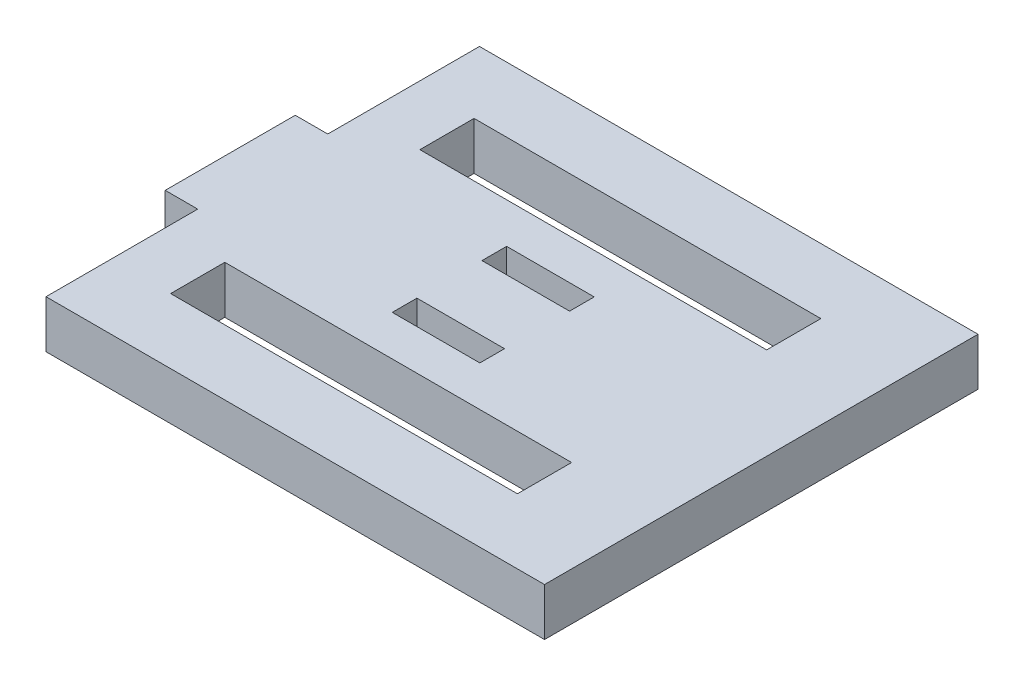
SolidWorks part; units mm, degrees
material "cardboard"
ref_plane "Front Plane" through (0, 0, 0) normal (0, 0, 1) x (1, 0, 0)
ref_plane "Top Plane" through (0, 0, 0) normal (0, 1, 0) x (1, 0, 0)
ref_plane "Right Plane" through (0, 0, 0) normal (1, 0, 0) x (0, 0, -1)
sketch "Sketch1" plane through (0, 0, 0) normal (0, 1, 0) x (1, 0, 0)
  line L0 (78.5546, 12.1341) -> (71.7044, 8.1792)
  line L1 (104.0546, -11.8659) -> (110.9047, -7.911)
  line L2 (119.2044, 8.1792) -> (110.9047, 8.1792)
  line L3 (119.2044, -7.911) -> (110.9047, -7.911)
  line L4 (71.7044, 8.1792) -> (63.4047, 8.1792)
  line L5 (126.0546, 12.1341) -> (119.2044, 8.1792)
  line L6 (126.0546, -11.8659) -> (119.2044, -7.911)
  line L7 (104.0546, 12.1341) -> (110.9047, 8.1792)
  line L8 (126.0546, 12.1341) -> (138.8046, 12.1341)
  line L9 (126.0546, -11.8659) -> (162.8046, -11.8659)
  line L10 (56.5546, 12.1341) -> (63.4047, 8.1792)
  line L11 (56.5546, -11.8659) -> (63.4047, -7.911)
  line L12 (78.5546, -11.8659) -> (71.7044, -7.911)
  line L13 (71.7044, -7.911) -> (63.4047, -7.911)
  line L14 (78.5546, 12.1341) -> (104.0546, 12.1341)
  line L15 (78.5546, -11.8659) -> (104.0546, -11.8659)
  line L16 (-11.1954, 77.8841) -> (-7.2405, 71.034)
  line L17 (12.8046, 103.3841) -> (8.8496, 110.2342)
  line L18 (-7.2405, 118.534) -> (-7.2405, 110.2342)
  line L19 (8.8496, 118.534) -> (8.8496, 110.2342)
  line L20 (-7.2405, 71.034) -> (-7.2405, 62.7342)
  line L21 (-11.1954, 125.3841) -> (-7.2405, 118.534)
  line L22 (12.8046, 125.3841) -> (8.8496, 118.534)
  line L23 (-11.1954, 103.3841) -> (-7.2405, 110.2342)
  line L24 (-11.1954, 125.3841) -> (-11.1954, 138.1341)
  line L25 (12.8046, 125.3841) -> (12.8046, 162.1341)
  line L26 (-11.1954, 55.8841) -> (-7.2405, 62.7342)
  line L27 (12.8046, 55.8841) -> (8.8496, 62.7342)
  line L28 (12.8046, 77.8841) -> (8.8496, 71.034)
  line L29 (8.8496, 71.034) -> (8.8496, 62.7342)
  line L30 (-11.1954, 77.8841) -> (-11.1954, 103.3841)
  line L31 (12.8046, 77.8841) -> (12.8046, 103.3841)
  line L32 (91.3046, 37.1341) -> (91.3046, 17.1341)
  line L33 (90.3046, 37.1341) -> (90.3046, 31.1341)
  line L34 (37.8046, 12.1341) -> (43.8046, 12.1341)
  line L35 (90.3046, 31.1341) -> (92.3046, 31.1341)
  line L36 (42.5546, 12.1341) -> (42.5546, 10.1341)
  line L37 (43.8046, 12.1341) -> (56.5546, 12.1341)
  line L38 (138.8046, 12.1341) -> (138.8046, -11.8659)
  line L39 (138.8046, 12.1341) -> (162.8046, 12.1341)
  line L40 (162.8046, 12.1341) -> (162.8046, 10.1341)
  line L41 (-27.6918, 14.4884) -> (0.8046, -14.008)
  line L42 (-27.6918, 14.4884) -> (-13.5497, 28.6305)
  line L43 (0.8046, -14.008) -> (14.9467, 0.1341)
  line L44 (-13.5497, 28.6305) -> (14.9467, 0.1341)
  line L45 (138.8046, 12.1341) -> (138.8046, 37.1341)
  line L46 (40.8046, 37.1341) -> (162.8046, 37.1341)
  line L47 (162.8046, 37.1341) -> (162.8046, 12.1341)
  line L48 (92.3046, 31.1341) -> (92.3046, 23.1341)
  line L49 (138.8046, 37.1341) -> (138.8046, 61.1341)
  line L50 (138.8046, 61.1341) -> (147.8046, 61.1341)
  line L51 (43.8046, 37.1341) -> (43.8046, 17.1341)
  line L52 (162.8046, 61.1341) -> (162.8046, 51.4561)
  line L53 (147.8046, 61.1341) -> (147.8046, 63.3341)
  line L54 (153.8046, 63.3341) -> (153.8046, 61.1341)
  line L55 (153.8046, 61.1341) -> (162.8046, 61.1341)
  line L56 (-58.1954, 138.1341) -> (-58.1954, 113.6341)
  line L57 (-38.1954, 113.6341) -> (-38.1954, 138.1341)
  line L58 (92.3046, 23.1341) -> (90.3046, 23.1341)
  line L59 (138.8046, -11.8659) -> (138.8046, -36.8659)
  line L60 (147.8046, -36.8659) -> (153.8046, -36.8659)
  line L61 (162.8046, -36.8659) -> (162.8046, -11.8659)
  line L62 (43.8046, -36.8659) -> (43.8046, -16.8659)
  line L63 (138.8046, -36.8659) -> (138.8046, -38.0459)
  line L64 (153.8046, -38.0459) -> (162.8046, -38.0459)
  line L65 (162.8046, -38.0459) -> (162.8046, -36.8659)
  line L66 (147.8046, -38.0459) -> (147.8046, -36.8659)
  line L67 (153.8046, -38.0459) -> (153.8046, -36.8659)
  line L68 (-37.3754, -137.8659) -> (-37.3754, -146.8659)
  line L69 (90.3046, 23.1341) -> (90.3046, 17.1341)
  line L70 (90.3046, 12.1341) -> (90.3046, 4.1341)
  line L71 (43.8046, -11.8659) -> (56.5546, -11.8659)
  line L72 (37.8046, -11.8659) -> (43.8046, -11.8659)
  line L73 (91.2784, 12.1341) -> (91.2784, -11.8659)
  line L74 (90.3046, 4.1341) -> (92.3046, 4.1341)
  line L75 (92.3046, 4.1341) -> (92.3046, -3.8659)
  line L76 (92.3046, -3.8659) -> (90.3046, -3.8659)
  line L77 (136.8046, 12.1341) -> (136.8046, 4.1341)
  line L78 (136.8046, 4.1341) -> (140.8046, 4.1341)
  line L79 (38.9846, 162.1341) -> (38.9846, 153.1341)
  line L80 (38.8046, 35.1341) -> (38.8046, 19.1341)
  line L81 (40.8046, 17.1341) -> (138.8046, 17.1341)
  line L82 (42.5546, 24.1341) -> (42.5546, 17.1341)
  line L83 (43.8046, 30.1341) -> (40.8046, 30.1341)
  line L84 (40.8046, 30.1341) -> (40.8046, 24.1341)
  line L85 (45.0546, 6.1341) -> (42.5546, 6.1341)
  line L86 (6.8046, -41.6159) -> (6.8046, -39.6159)
  line L87 (42.5546, -5.8659) -> (45.0546, -5.8659)
  line L88 (45.0546, 6.1341) -> (45.0546, -5.8659)
  line L89 (43.8046, 12.1341) -> (43.8046, 6.1341)
  line L90 (42.5546, 10.1341) -> (45.0546, 10.1341)
  line L91 (45.0546, 10.1341) -> (45.0546, 8.1341)
  line L92 (45.0546, 8.1341) -> (42.5546, 8.1341)
  line L93 (42.5546, 8.1341) -> (42.5546, 6.1341)
  line L94 (42.5546, -7.8659) -> (42.5546, -5.8659)
  line L95 (45.0546, -7.8659) -> (42.5546, -7.8659)
  line L96 (45.0546, -9.8659) -> (45.0546, -7.8659)
  line L97 (42.5546, -9.8659) -> (45.0546, -9.8659)
  line L98 (42.5546, -11.8659) -> (42.5546, -9.8659)
  line L99 (140.8046, 4.1341) -> (140.8046, -3.8659)
  line L100 (140.8046, -3.8659) -> (136.8046, -3.8659)
  line L101 (136.8046, -3.8659) -> (136.8046, -11.8659)
  line L102 (138.8046, 14.1341) -> (146.8046, 14.1341)
  line L103 (146.8046, 14.1341) -> (146.8046, 10.1341)
  line L104 (146.8046, 10.1341) -> (154.8046, 10.1341)
  line L105 (154.8046, 10.1341) -> (154.8046, 14.1341)
  line L106 (154.8046, 14.1341) -> (162.8046, 14.1341)
  line L107 (137.3046, 37.1341) -> (137.3046, 31.1341)
  line L108 (137.3046, 31.1341) -> (140.3046, 31.1341)
  line L109 (140.3046, 31.1341) -> (140.3046, 23.1341)
  line L110 (140.3046, 23.1341) -> (137.3046, 23.1341)
  line L111 (137.3046, 23.1341) -> (137.3046, 17.1341)
  line L112 (90.3046, -3.8659) -> (90.3046, -11.8659)
  line L113 (90.3046, -22.8659) -> (90.3046, -16.8659)
  line L114 (91.3046, -36.8659) -> (91.3046, -16.8659)
  line L115 (92.3046, -22.8659) -> (90.3046, -22.8659)
  line L116 (92.3046, -30.8659) -> (92.3046, -22.8659)
  line L117 (154.8046, -13.8659) -> (162.8046, -13.8659)
  line L118 (154.8046, -9.8659) -> (154.8046, -13.8659)
  line L119 (146.8046, -9.8659) -> (154.8046, -9.8659)
  line L120 (146.8046, -13.8659) -> (146.8046, -9.8659)
  line L121 (138.8046, -13.8659) -> (146.8046, -13.8659)
  line L122 (137.3046, -22.8659) -> (137.3046, -16.8659)
  line L123 (140.3046, -22.8659) -> (137.3046, -22.8659)
  line L124 (42.5546, 37.1341) -> (42.5546, 30.1341)
  line L125 (43.8046, 24.1341) -> (40.8046, 24.1341)
  line L126 (138.8046, -36.8659) -> (40.8046, -36.8659)
  line L127 (38.8046, -34.8659) -> (38.8046, -18.8659)
  line L128 (40.8046, -16.8659) -> (138.8046, -16.8659)
  line L129 (140.3046, -30.8659) -> (140.3046, -22.8659)
  line L130 (137.3046, -30.8659) -> (140.3046, -30.8659)
  line L131 (137.3046, -36.8659) -> (137.3046, -30.8659)
  line L132 (90.3046, -30.8659) -> (92.3046, -30.8659)
  line L133 (90.3046, -36.8659) -> (90.3046, -30.8659)
  line L134 (138.8046, 39.1341) -> (146.8046, 39.1341)
  line L135 (146.8046, 39.1341) -> (146.8046, 35.1341)
  line L136 (146.8046, 35.1341) -> (154.8046, 35.1341)
  line L137 (154.8046, 35.1341) -> (154.8046, 39.1341)
  line L138 (154.8046, 39.1341) -> (162.8046, 39.1341)
  line L139 (-43.6954, 133.8841) -> (-43.6954, 117.8841)
  line L140 (-55.1954, 133.8841) -> (-52.6954, 133.8841)
  line L141 (-55.1954, 133.8841) -> (-55.1954, 117.8841)
  line L142 (-55.1954, 117.8841) -> (-52.6954, 117.8841)
  line L143 (-52.6954, 133.8841) -> (-52.6954, 117.8841)
  line L144 (42.5546, -23.8659) -> (42.5546, -16.8659)
  line L145 (43.8046, -23.8659) -> (40.8046, -23.8659)
  line L146 (40.8046, -29.8659) -> (40.8046, -23.8659)
  line L147 (43.8046, -29.8659) -> (40.8046, -29.8659)
  line L148 (42.5546, -36.8659) -> (42.5546, -29.8659)
  line L149 (197.8046, 5.1341) -> (197.8046, -4.8659)
  line L150 (192.8046, 10.1341) -> (162.8046, 10.1341)
  line L151 (192.8046, -9.8659) -> (162.8046, -9.8659)
  line L152 (192.8046, 10.1341) -> (197.8046, 5.1341)
  line L153 (197.8046, -4.8659) -> (192.8046, -9.8659)
  line L154 (162.8046, -9.8659) -> (162.8046, -11.8659)
  line L155 (138.8046, 63.3341) -> (147.8046, 63.3341)
  line L156 (138.8046, 63.3341) -> (138.8046, 65.3341)
  line L157 (138.8046, 65.3341) -> (162.8046, 65.3341)
  line L158 (162.8046, 65.3341) -> (162.8046, 63.3341)
  line L159 (153.8046, 63.3341) -> (162.8046, 63.3341)
  line L160 (-41.1954, 117.8841) -> (-43.6954, 117.8841)
  line L161 (-41.1954, 133.8841) -> (-41.1954, 117.8841)
  line L162 (-41.1954, 133.8841) -> (-43.6954, 133.8841)
  line L163 (156.2046, 51.4561) -> (162.8046, 51.4561)
  line L164 (156.2046, 51.4561) -> (156.2046, 46.9561)
  line L165 (156.2046, 46.9561) -> (162.8046, 46.9561)
  line L166 (162.8046, 46.9561) -> (162.8046, 37.1341)
  line L167 (12.8046, -77.6159) -> (8.8496, -70.7658)
  line L168 (-11.1954, -103.1159) -> (-7.2405, -109.966)
  line L169 (8.8496, -118.2658) -> (8.8496, -109.966)
  line L170 (12.8046, -36.8659) -> (12.8046, -42.8659)
  line L171 (12.8046, -41.6159) -> (10.8046, -41.6159)
  line L172 (12.8046, -42.8659) -> (12.8046, -55.6159)
  line L173 (-7.2405, -118.2658) -> (-7.2405, -109.966)
  line L174 (8.8496, -70.7658) -> (8.8496, -62.466)
  line L175 (12.8046, -125.1159) -> (8.8496, -118.2658)
  line L176 (-11.1954, -125.1159) -> (-7.2405, -118.2658)
  line L177 (12.8046, -103.1159) -> (8.8496, -109.966)
  line L178 (12.8046, -125.1159) -> (12.8046, -137.8659)
  line L179 (-11.1954, -125.1159) -> (-11.1954, -161.8659)
  line L180 (12.8046, -55.6159) -> (8.8496, -62.466)
  line L181 (-11.1954, -55.6159) -> (-7.2405, -62.466)
  line L182 (37.8046, -42.8659) -> (17.8046, -42.8659)
  line L183 (-11.1954, -77.6159) -> (-7.2405, -70.7658)
  line L184 (-7.2405, -70.7658) -> (-7.2405, -62.466)
  line L185 (12.8046, -77.6159) -> (12.8046, -103.1159)
  line L186 (-11.1954, -77.6159) -> (-11.1954, -103.1159)
  line L187 (37.8046, -90.3659) -> (17.8046, -90.3659)
  line L188 (37.8046, -89.3659) -> (31.8046, -89.3659)
  line L189 (31.8046, -89.3659) -> (31.8046, -91.3659)
  line L190 (12.8046, -137.8659) -> (-11.1954, -137.8659)
  line L191 (12.8046, -137.8659) -> (12.8046, -161.8659)
  line L192 (12.8046, -161.8659) -> (10.8046, -161.8659)
  line L193 (12.8046, -137.8659) -> (37.8046, -137.8659)
  line L194 (37.8046, -39.8659) -> (37.8046, -161.8659)
  line L195 (-36.1954, -42.8659) -> (-16.1954, -42.8659)
  line L196 (37.8046, -161.8659) -> (12.8046, -161.8659)
  line L197 (31.8046, -91.3659) -> (23.8046, -91.3659)
  line L198 (37.8046, -137.8659) -> (61.8046, -137.8659)
  line L199 (61.8046, -137.8659) -> (61.8046, -146.8659)
  line L200 (61.8046, -161.8659) -> (52.1265, -161.8659)
  line L201 (61.8046, -146.8659) -> (64.0046, -146.8659)
  line L202 (64.0046, -152.8659) -> (61.8046, -152.8659)
  line L203 (61.8046, -152.8659) -> (61.8046, -161.8659)
  line L204 (-11.1954, -42.8659) -> (-11.1954, -55.6159)
  line L205 (-11.1954, -36.8659) -> (-11.1954, -42.8659)
  line L206 (23.8046, -91.3659) -> (23.8046, -89.3659)
  line L207 (-11.1954, -137.8659) -> (-36.1954, -137.8659)
  line L208 (-36.1954, -146.8659) -> (-36.1954, -152.8659)
  line L209 (38.9846, 147.1341) -> (38.9846, 138.1341)
  line L210 (35.8046, -37.8659) -> (19.8046, -37.8659)
  line L211 (17.8046, -39.8659) -> (17.8046, -137.8659)
  line L212 (24.8046, -41.6159) -> (17.8046, -41.6159)
  line L213 (30.8046, -42.8659) -> (30.8046, -39.8659)
  line L214 (30.8046, -39.8659) -> (24.8046, -39.8659)
  line L215 (6.8046, -44.1159) -> (6.8046, -41.6159)
  line L216 (-36.1954, -161.8659) -> (-11.1954, -161.8659)
  line L217 (-5.1954, -41.6159) -> (-5.1954, -44.1159)
  line L218 (6.8046, -44.1159) -> (-5.1954, -44.1159)
  line L219 (12.8046, -42.8659) -> (6.8046, -42.8659)
  line L220 (10.8046, -41.6159) -> (10.8046, -44.1159)
  line L221 (10.8046, -44.1159) -> (8.8046, -44.1159)
  line L222 (8.8046, -44.1159) -> (8.8046, -41.6159)
  line L223 (8.8046, -41.6159) -> (6.8046, -41.6159)
  line L224 (-7.1954, -41.6159) -> (-5.1954, -41.6159)
  line L225 (-7.1954, -44.1159) -> (-7.1954, -41.6159)
  line L226 (-9.1954, -44.1159) -> (-7.1954, -44.1159)
  line L227 (-9.1954, -41.6159) -> (-9.1954, -44.1159)
  line L228 (-11.1954, -41.6159) -> (-9.1954, -41.6159)
  line L229 (-36.1954, -137.8659) -> (-37.3754, -137.8659)
  line L230 (-37.3754, -152.8659) -> (-37.3754, -161.8659)
  line L231 (-37.3754, -161.8659) -> (-36.1954, -161.8659)
  line L232 (-37.3754, -146.8659) -> (-36.1954, -146.8659)
  line L233 (-37.3754, -152.8659) -> (-36.1954, -152.8659)
  line L234 (-161.1954, 38.3141) -> (-152.1954, 38.3141)
  line L235 (23.8046, -89.3659) -> (17.8046, -89.3659)
  line L236 (12.8046, -89.3659) -> (4.8046, -89.3659)
  line L237 (12.8046, -90.3397) -> (-11.1954, -90.3397)
  line L238 (4.8046, -89.3659) -> (4.8046, -91.3659)
  line L239 (4.8046, -91.3659) -> (-3.1954, -91.3659)
  line L240 (-3.1954, -91.3659) -> (-3.1954, -89.3659)
  line L241 (12.8046, -135.8659) -> (4.8046, -135.8659)
  line L242 (4.8046, -135.8659) -> (4.8046, -139.8659)
  line L243 (4.8046, -139.8659) -> (-3.1954, -139.8659)
  line L244 (-3.1954, -139.8659) -> (-3.1954, -135.8659)
  line L245 (-3.1954, -135.8659) -> (-11.1954, -135.8659)
  line L246 (14.8046, -137.8659) -> (14.8046, -145.8659)
  line L247 (14.8046, -145.8659) -> (10.8046, -145.8659)
  line L248 (10.8046, -145.8659) -> (10.8046, -153.8659)
  line L249 (10.8046, -153.8659) -> (14.8046, -153.8659)
  line L250 (14.8046, -153.8659) -> (14.8046, -161.8659)
  line L251 (37.8046, -136.3659) -> (31.8046, -136.3659)
  line L252 (31.8046, -136.3659) -> (31.8046, -139.3659)
  line L253 (31.8046, -139.3659) -> (23.8046, -139.3659)
  line L254 (37.8046, -41.6159) -> (30.8046, -41.6159)
  line L255 (24.8046, -42.8659) -> (24.8046, -39.8659)
  line L256 (-36.1954, -137.8659) -> (-36.1954, -39.8659)
  line L257 (-34.1954, -37.8659) -> (-18.1954, -37.8659)
  line L258 (-16.1954, -39.8659) -> (-16.1954, -137.8659)
  line L259 (23.8046, -139.3659) -> (23.8046, -136.3659)
  line L260 (23.8046, -136.3659) -> (17.8046, -136.3659)
  line L261 (-3.1954, -89.3659) -> (-11.1954, -89.3659)
  line L262 (-22.1954, -89.3659) -> (-16.1954, -89.3659)
  line L263 (-36.1954, -90.3659) -> (-16.1954, -90.3659)
  line L264 (-22.1954, -91.3659) -> (-22.1954, -89.3659)
  line L265 (-30.1954, -91.3659) -> (-22.1954, -91.3659)
  line L266 (-13.1954, -153.8659) -> (-13.1954, -161.8659)
  line L267 (-9.1954, -153.8659) -> (-13.1954, -153.8659)
  line L268 (-9.1954, -145.8659) -> (-9.1954, -153.8659)
  line L269 (-13.1954, -145.8659) -> (-9.1954, -145.8659)
  line L270 (-13.1954, -137.8659) -> (-13.1954, -145.8659)
  line L271 (-22.1954, -136.3659) -> (-16.1954, -136.3659)
  line L272 (-22.1954, -139.3659) -> (-22.1954, -136.3659)
  line L273 (-30.1954, -139.3659) -> (-22.1954, -139.3659)
  line L274 (-23.1954, -41.6159) -> (-16.1954, -41.6159)
  line L275 (-23.1954, -42.8659) -> (-23.1954, -39.8659)
  line L276 (-29.1954, -39.8659) -> (-23.1954, -39.8659)
  line L277 (-29.1954, -42.8659) -> (-29.1954, -39.8659)
  line L278 (-36.1954, -41.6159) -> (-29.1954, -41.6159)
  line L279 (-30.1954, -136.3659) -> (-30.1954, -139.3659)
  line L280 (-36.1954, -136.3659) -> (-30.1954, -136.3659)
  line L281 (-30.1954, -89.3659) -> (-30.1954, -91.3659)
  line L282 (-36.1954, -89.3659) -> (-30.1954, -89.3659)
  line L283 (39.8046, -137.8659) -> (39.8046, -145.8659)
  line L284 (39.8046, -145.8659) -> (35.8046, -145.8659)
  line L285 (35.8046, -145.8659) -> (35.8046, -153.8659)
  line L286 (35.8046, -153.8659) -> (39.8046, -153.8659)
  line L287 (39.8046, -153.8659) -> (39.8046, -161.8659)
  line L288 (5.8046, -196.8659) -> (-4.1954, -196.8659)
  line L289 (10.8046, -191.8659) -> (10.8046, -161.8659)
  line L290 (-9.1954, -191.8659) -> (-9.1954, -161.8659)
  line L291 (10.8046, -191.8659) -> (5.8046, -196.8659)
  line L292 (-4.1954, -196.8659) -> (-9.1954, -191.8659)
  line L293 (-9.1954, -161.8659) -> (-11.1954, -161.8659)
  line L294 (64.0046, -137.8659) -> (64.0046, -146.8659)
  line L295 (64.0046, -137.8659) -> (66.0046, -137.8659)
  line L296 (66.0046, -137.8659) -> (66.0046, -161.8659)
  line L297 (66.0046, -161.8659) -> (64.0046, -161.8659)
  line L298 (64.0046, -152.8659) -> (64.0046, -161.8659)
  line L299 (-36.1954, -11.8659) -> (-42.1954, -11.8659)
  line L300 (-40.9454, -11.8659) -> (-40.9454, -9.8659)
  line L301 (-42.1954, -11.8659) -> (-54.9454, -11.8659)
  line L302 (52.1265, -155.2659) -> (52.1265, -161.8659)
  line L303 (52.1265, -155.2659) -> (47.6265, -155.2659)
  line L304 (-42.1954, -36.8659) -> (-42.1954, -16.8659)
  line L305 (47.6265, -155.2659) -> (47.6265, -161.8659)
  line L306 (47.6265, -161.8659) -> (37.8046, -161.8659)
  line L307 (-76.9454, -11.8659) -> (-70.0953, -7.911)
  line L308 (-102.4454, 12.1341) -> (-109.2956, 8.1792)
  line L309 (-117.5953, -7.911) -> (-109.2956, -7.911)
  line L310 (-117.5953, 8.1792) -> (-109.2956, 8.1792)
  line L311 (-70.0953, -7.911) -> (-61.7956, -7.911)
  line L312 (-124.4454, -11.8659) -> (-117.5953, -7.911)
  line L313 (-124.4454, 12.1341) -> (-117.5953, 8.1792)
  line L314 (-102.4454, -11.8659) -> (-109.2956, -7.911)
  line L315 (-124.4454, -11.8659) -> (-137.1954, -11.8659)
  line L316 (-42.1954, 37.1341) -> (-42.1954, 17.1341)
  line L317 (-124.4454, 12.1341) -> (-161.1954, 12.1341)
  line L318 (-54.9454, -11.8659) -> (-61.7956, -7.911)
  line L319 (-54.9454, 12.1341) -> (-61.7956, 8.1792)
  line L320 (-76.9454, 12.1341) -> (-70.0953, 8.1792)
  line L321 (-70.0953, 8.1792) -> (-61.7956, 8.1792)
  line L322 (-76.9454, -11.8659) -> (-102.4454, -11.8659)
  line L323 (-76.9454, 12.1341) -> (-102.4454, 12.1341)
  line L324 (-89.6954, -36.8659) -> (-89.6954, -16.8659)
  line L325 (-42.1954, 12.1341) -> (-54.9454, 12.1341)
  line L326 (-36.1954, 12.1341) -> (-42.1954, 12.1341)
  line L327 (-88.6954, -36.8659) -> (-88.6954, -30.8659)
  line L328 (-88.6954, -30.8659) -> (-90.6954, -30.8659)
  line L329 (-137.1954, -11.8659) -> (-137.1954, 12.1341)
  line L330 (-137.1954, -11.8659) -> (-161.1954, -11.8659)
  line L331 (-161.1954, -11.8659) -> (-161.1954, -9.8659)
  line L332 (-137.1954, -11.8659) -> (-137.1954, -36.8659)
  line L333 (138.8046, -38.0459) -> (147.8046, -38.0459)
  line L334 (-37.1954, -34.8659) -> (-37.1954, -18.8659)
  line L335 (-39.1954, -16.8659) -> (-137.1954, -16.8659)
  line L336 (-40.9454, -23.8659) -> (-40.9454, -16.8659)
  line L337 (-42.1954, -29.8659) -> (-39.1954, -29.8659)
  line L338 (-39.1954, -29.8659) -> (-39.1954, -23.8659)
  line L339 (-43.4454, -5.8659) -> (-40.9454, -5.8659)
  line L340 (-39.1954, -36.8659) -> (-161.1954, -36.8659)
  line L341 (-40.9454, 6.1341) -> (-43.4454, 6.1341)
  line L342 (-43.4454, -5.8659) -> (-43.4454, 6.1341)
  line L343 (-42.1954, -11.8659) -> (-42.1954, -5.8659)
  line L344 (-40.9454, -9.8659) -> (-43.4454, -9.8659)
  line L345 (-43.4454, -9.8659) -> (-43.4454, -7.8659)
  line L346 (-43.4454, -7.8659) -> (-40.9454, -7.8659)
  line L347 (-40.9454, -7.8659) -> (-40.9454, -5.8659)
  line L348 (-40.9454, 8.1341) -> (-40.9454, 6.1341)
  line L349 (-43.4454, 8.1341) -> (-40.9454, 8.1341)
  line L350 (-43.4454, 10.1341) -> (-43.4454, 8.1341)
  line L351 (-40.9454, 10.1341) -> (-43.4454, 10.1341)
  line L352 (-40.9454, 12.1341) -> (-40.9454, 10.1341)
  line L353 (-161.1954, -36.8659) -> (-161.1954, -11.8659)
  line L354 (-90.6954, -30.8659) -> (-90.6954, -22.8659)
  line L355 (-137.1954, -36.8659) -> (-137.1954, -60.8659)
  line L356 (-137.1954, -60.8659) -> (-146.1954, -60.8659)
  line L357 (-161.1954, -60.8659) -> (-161.1954, -51.1879)
  line L358 (-146.1954, -60.8659) -> (-146.1954, -63.0659)
  line L359 (-152.1954, -63.0659) -> (-152.1954, -60.8659)
  line L360 (-152.1954, -60.8659) -> (-161.1954, -60.8659)
  line L361 (-90.6954, -22.8659) -> (-88.6954, -22.8659)
  line L362 (-137.1954, 12.1341) -> (-137.1954, 37.1341)
  line L363 (-146.1954, 37.1341) -> (-152.1954, 37.1341)
  line L364 (-161.1954, 37.1341) -> (-161.1954, 12.1341)
  line L365 (-137.1954, 37.1341) -> (-137.1954, 38.3141)
  line L366 (-161.1954, 38.3141) -> (-161.1954, 37.1341)
  line L367 (-146.1954, 38.3141) -> (-146.1954, 37.1341)
  line L368 (-152.1954, 38.3141) -> (-152.1954, 37.1341)
  line L369 (-146.1954, 38.3141) -> (-137.1954, 38.3141)
  line L370 (-88.6954, -22.8659) -> (-88.6954, -16.8659)
  line L371 (-88.6954, -11.8659) -> (-88.6954, -3.8659)
  line L372 (-89.6692, -11.8659) -> (-89.6692, 12.1341)
  line L373 (-88.6954, -3.8659) -> (-90.6954, -3.8659)
  line L374 (-40.9454, -36.8659) -> (-40.9454, -29.8659)
  line L375 (-42.1954, -23.8659) -> (-39.1954, -23.8659)
  line L376 (-137.1954, 37.1341) -> (-39.1954, 37.1341)
  line L377 (-37.1954, 35.1341) -> (-37.1954, 19.1341)
  line L378 (-39.1954, 17.1341) -> (-137.1954, 17.1341)
  line L379 (-90.6954, -3.8659) -> (-90.6954, 4.1341)
  line L380 (-90.6954, 4.1341) -> (-88.6954, 4.1341)
  line L381 (-135.1954, -11.8659) -> (-135.1954, -3.8659)
  line L382 (-135.1954, -3.8659) -> (-139.1954, -3.8659)
  line L383 (-139.1954, -3.8659) -> (-139.1954, 4.1341)
  line L384 (-139.1954, 4.1341) -> (-135.1954, 4.1341)
  line L385 (-135.1954, 4.1341) -> (-135.1954, 12.1341)
  line L386 (-137.1954, -13.8659) -> (-145.1954, -13.8659)
  line L387 (-145.1954, -13.8659) -> (-145.1954, -9.8659)
  line L388 (-145.1954, -9.8659) -> (-153.1954, -9.8659)
  line L389 (-153.1954, -9.8659) -> (-153.1954, -13.8659)
  line L390 (-153.1954, -13.8659) -> (-161.1954, -13.8659)
  line L391 (-135.6954, -36.8659) -> (-135.6954, -30.8659)
  line L392 (-36.1954, 90.6341) -> (-16.1954, 90.6341)
  line L393 (-36.1954, 89.6341) -> (-30.1954, 89.6341)
  line L394 (-40.9454, 24.1341) -> (-40.9454, 17.1341)
  line L395 (-42.1954, 24.1341) -> (-39.1954, 24.1341)
  line L396 (-39.1954, 30.1341) -> (-39.1954, 24.1341)
  line L397 (-42.1954, 30.1341) -> (-39.1954, 30.1341)
  line L398 (-40.9454, 37.1341) -> (-40.9454, 30.1341)
  line L399 (-135.6954, -30.8659) -> (-138.6954, -30.8659)
  line L400 (-138.6954, -30.8659) -> (-138.6954, -22.8659)
  line L401 (-138.6954, -22.8659) -> (-135.6954, -22.8659)
  line L402 (-135.6954, -22.8659) -> (-135.6954, -16.8659)
  line L403 (-88.6954, 4.1341) -> (-88.6954, 12.1341)
  line L404 (-88.6954, 23.1341) -> (-88.6954, 17.1341)
  line L405 (-89.6954, 37.1341) -> (-89.6954, 17.1341)
  line L406 (-90.6954, 23.1341) -> (-88.6954, 23.1341)
  line L407 (-90.6954, 31.1341) -> (-90.6954, 23.1341)
  line L408 (-153.1954, 14.1341) -> (-161.1954, 14.1341)
  line L409 (-153.1954, 10.1341) -> (-153.1954, 14.1341)
  line L410 (-145.1954, 10.1341) -> (-153.1954, 10.1341)
  line L411 (-145.1954, 14.1341) -> (-145.1954, 10.1341)
  line L412 (-137.1954, 14.1341) -> (-145.1954, 14.1341)
  line L413 (-135.6954, 23.1341) -> (-135.6954, 17.1341)
  line L414 (-138.6954, 23.1341) -> (-135.6954, 23.1341)
  line L415 (-138.6954, 31.1341) -> (-138.6954, 23.1341)
  line L416 (-135.6954, 31.1341) -> (-138.6954, 31.1341)
  line L417 (-135.6954, 37.1341) -> (-135.6954, 31.1341)
  line L418 (-88.6954, 31.1341) -> (-90.6954, 31.1341)
  line L419 (-88.6954, 37.1341) -> (-88.6954, 31.1341)
  line L420 (-137.1954, -38.8659) -> (-145.1954, -38.8659)
  line L421 (-145.1954, -38.8659) -> (-145.1954, -34.8659)
  line L422 (-145.1954, -34.8659) -> (-153.1954, -34.8659)
  line L423 (-153.1954, -34.8659) -> (-153.1954, -38.8659)
  line L424 (-153.1954, -38.8659) -> (-161.1954, -38.8659)
  line L425 (-11.1954, 41.8841) -> (-9.1954, 41.8841)
  line L426 (-30.1954, 89.6341) -> (-30.1954, 91.6341)
  line L427 (-11.1954, 138.1341) -> (12.8046, 138.1341)
  line L428 (-11.1954, 138.1341) -> (-11.1954, 162.1341)
  line L429 (-11.1954, 162.1341) -> (-9.1954, 162.1341)
  line L430 (-11.1954, 138.1341) -> (-36.1954, 138.1341)
  line L431 (-36.1954, 138.1341) -> (-36.1954, 162.1341)
  line L432 (-36.1954, 162.1341) -> (-11.1954, 162.1341)
  line L433 (-36.1954, 138.1341) -> (-36.1954, 43.1341)
  line L434 (-36.1954, 43.1341) -> (-16.1954, 43.1341)
  line L435 (-16.1954, 43.1341) -> (-16.1954, 138.1341)
  line L436 (-30.1954, 91.6341) -> (-22.1954, 91.6341)
  line L437 (-36.1954, 138.1341) -> (-60.1954, 138.1341)
  line L438 (-60.1954, 138.1341) -> (-60.1954, 147.1341)
  line L439 (-60.1954, 162.1341) -> (-50.5174, 162.1341)
  line L440 (-60.1954, 147.1341) -> (-62.3954, 147.1341)
  line L441 (-62.3954, 153.1341) -> (-60.1954, 153.1341)
  line L442 (-60.1954, 153.1341) -> (-60.1954, 162.1341)
  line L443 (-58.1954, 113.6341) -> (-38.1954, 113.6341)
  line L444 (37.8046, 43.1341) -> (17.8046, 43.1341)
  line L445 (-22.1954, 91.6341) -> (-22.1954, 89.6341)
  line L446 (37.8046, 138.1341) -> (37.8046, 43.1341)
  line L447 (17.8046, 43.1341) -> (17.8046, 138.1341)
  line L448 (12.8046, 138.1341) -> (37.8046, 138.1341)
  line L449 (37.8046, 147.1341) -> (37.8046, 153.1341)
  line L450 (37.8046, 162.1341) -> (12.8046, 162.1341)
  line L451 (12.8046, 37.1341) -> (12.8046, 55.8841)
  line L452 (37.8046, 138.1341) -> (38.9846, 138.1341)
  line L453 (38.9846, 162.1341) -> (37.8046, 162.1341)
  line L454 (38.9846, 147.1341) -> (37.8046, 147.1341)
  line L455 (38.9846, 153.1341) -> (37.8046, 153.1341)
  line L456 (-36.1954, 43.1341) -> (-36.1954, 40.1341)
  line L457 (-34.1954, 38.1341) -> (-18.1954, 38.1341)
  line L458 (-16.1954, 40.1341) -> (-16.1954, 43.1341)
  line L459 (35.8046, 38.1341) -> (19.8046, 38.1341)
  line L460 (17.8046, 40.1341) -> (17.8046, 43.1341)
  line L461 (-5.1954, 44.3841) -> (-5.1954, 41.8841)
  line L462 (-22.1954, 89.6341) -> (-16.1954, 89.6341)
  line L463 (6.8046, 41.8841) -> (6.8046, 44.3841)
  line L464 (-5.1954, 44.3841) -> (6.8046, 44.3841)
  line L465 (-11.1954, 43.1341) -> (-5.1954, 43.1341)
  line L466 (-9.1954, 41.8841) -> (-9.1954, 44.3841)
  line L467 (-9.1954, 44.3841) -> (-7.1954, 44.3841)
  line L468 (-7.1954, 44.3841) -> (-7.1954, 41.8841)
  line L469 (-7.1954, 41.8841) -> (-5.1954, 41.8841)
  line L470 (8.8046, 41.8841) -> (6.8046, 41.8841)
  line L471 (8.8046, 44.3841) -> (8.8046, 41.8841)
  line L472 (10.8046, 44.3841) -> (8.8046, 44.3841)
  line L473 (10.8046, 41.8841) -> (10.8046, 44.3841)
  line L474 (12.8046, 41.8841) -> (10.8046, 41.8841)
  line L475 (-11.1954, 89.6341) -> (-3.1954, 89.6341)
  line L476 (-11.1954, 90.6079) -> (12.8046, 90.6079)
  line L477 (-3.1954, 89.6341) -> (-3.1954, 91.6341)
  line L478 (-3.1954, 91.6341) -> (4.8046, 91.6341)
  line L479 (4.8046, 91.6341) -> (4.8046, 89.6341)
  line L480 (-11.1954, 136.1341) -> (-3.1954, 136.1341)
  line L481 (-3.1954, 136.1341) -> (-3.1954, 140.1341)
  line L482 (-3.1954, 140.1341) -> (4.8046, 140.1341)
  line L483 (4.8046, 140.1341) -> (4.8046, 136.1341)
  line L484 (4.8046, 136.1341) -> (12.8046, 136.1341)
  line L485 (-13.1954, 138.1341) -> (-13.1954, 146.1341)
  line L486 (-13.1954, 146.1341) -> (-9.1954, 146.1341)
  line L487 (-9.1954, 146.1341) -> (-9.1954, 154.1341)
  line L488 (-9.1954, 154.1341) -> (-13.1954, 154.1341)
  line L489 (-13.1954, 154.1341) -> (-13.1954, 162.1341)
  line L490 (-36.1954, 136.6341) -> (-30.1954, 136.6341)
  line L491 (-30.1954, 136.6341) -> (-30.1954, 139.6341)
  line L492 (-30.1954, 139.6341) -> (-22.1954, 139.6341)
  line L493 (-22.1954, 139.6341) -> (-22.1954, 136.6341)
  line L494 (-22.1954, 136.6341) -> (-16.1954, 136.6341)
  line L495 (4.8046, 89.6341) -> (12.8046, 89.6341)
  line L496 (23.8046, 89.6341) -> (17.8046, 89.6341)
  line L497 (37.8046, 90.6341) -> (17.8046, 90.6341)
  line L498 (23.8046, 91.6341) -> (23.8046, 89.6341)
  line L499 (31.8046, 91.6341) -> (23.8046, 91.6341)
  line L500 (-36.1954, 41.8841) -> (-29.1954, 41.8841)
  line L501 (30.8046, 40.1341) -> (24.8046, 40.1341)
  line L502 (24.8046, 41.8841) -> (17.8046, 41.8841)
  line L503 (-29.1954, 43.1341) -> (-29.1954, 40.1341)
  line L504 (-23.1954, 41.8841) -> (-16.1954, 41.8841)
  line L505 (14.8046, 154.1341) -> (14.8046, 162.1341)
  line L506 (10.8046, 154.1341) -> (14.8046, 154.1341)
  line L507 (10.8046, 146.1341) -> (10.8046, 154.1341)
  line L508 (14.8046, 146.1341) -> (10.8046, 146.1341)
  line L509 (14.8046, 138.1341) -> (14.8046, 146.1341)
  line L510 (23.8046, 136.6341) -> (17.8046, 136.6341)
  line L511 (23.8046, 139.6341) -> (23.8046, 136.6341)
  line L512 (31.8046, 139.6341) -> (23.8046, 139.6341)
  line L513 (31.8046, 136.6341) -> (31.8046, 139.6341)
  line L514 (37.8046, 136.6341) -> (31.8046, 136.6341)
  line L515 (31.8046, 89.6341) -> (31.8046, 91.6341)
  line L516 (37.8046, 89.6341) -> (31.8046, 89.6341)
  line L517 (12.8046, 37.1341) -> (21.769, 28.1696)
  line L518 (37.8046, -11.8659) -> (28.8401, -20.8304)
  line L519 (-11.1954, -36.8659) -> (-20.1599, -27.9014)
  line L520 (24.8046, 43.1341) -> (24.8046, 40.1341)
  line L521 (-23.1954, 43.1341) -> (-23.1954, 40.1341)
  line L522 (30.8046, 43.1341) -> (30.8046, 40.1341)
  line L523 (37.8046, 41.8841) -> (30.8046, 41.8841)
  line L524 (-38.1954, 138.1341) -> (-38.1954, 146.1341)
  line L525 (-38.1954, 146.1341) -> (-34.1954, 146.1341)
  line L526 (-34.1954, 146.1341) -> (-34.1954, 154.1341)
  line L527 (-34.1954, 154.1341) -> (-38.1954, 154.1341)
  line L528 (-38.1954, 154.1341) -> (-38.1954, 162.1341)
  line L529 (-58.1954, 136.6341) -> (-51.1954, 136.6341)
  line L530 (-51.1954, 136.6341) -> (-51.1954, 139.6341)
  line L531 (-51.1954, 139.6341) -> (-45.1954, 139.6341)
  line L532 (-45.1954, 139.6341) -> (-45.1954, 136.6341)
  line L533 (-45.1954, 136.6341) -> (-38.1954, 136.6341)
  line L534 (-11.1954, 37.1341) -> (-11.1954, 55.8841)
  line L535 (43.8046, -5.8659) -> (43.8046, -11.8659)
  line L536 (6.8046, 43.1341) -> (12.8046, 43.1341)
  line L537 (-42.1954, 6.1341) -> (-42.1954, 12.1341)
  line L538 (-5.1954, -42.8659) -> (-11.1954, -42.8659)
  line L539 (-4.1954, 197.1341) -> (5.8046, 197.1341)
  line L540 (-9.1954, 192.1341) -> (-9.1954, 162.1341)
  line L541 (10.8046, 192.1341) -> (10.8046, 162.1341)
  line L542 (-9.1954, 192.1341) -> (-4.1954, 197.1341)
  line L543 (5.8046, 197.1341) -> (10.8046, 192.1341)
  line L544 (134.5546, 56.1341) -> (118.5546, 56.1341)
  line L545 (134.5546, 56.1341) -> (134.5546, 53.6341)
  line L546 (-196.1954, -4.8659) -> (-196.1954, 5.1341)
  line L547 (-191.1954, -9.8659) -> (-161.1954, -9.8659)
  line L548 (-191.1954, 10.1341) -> (-161.1954, 10.1341)
  line L549 (-191.1954, -9.8659) -> (-196.1954, -4.8659)
  line L550 (-196.1954, 5.1341) -> (-191.1954, 10.1341)
  line L551 (-161.1954, 10.1341) -> (-161.1954, 12.1341)
  line L552 (-137.1954, -63.0659) -> (-146.1954, -63.0659)
  line L553 (-137.1954, -63.0659) -> (-137.1954, -65.0659)
  line L554 (-137.1954, -65.0659) -> (-161.1954, -65.0659)
  line L555 (-161.1954, -65.0659) -> (-161.1954, -63.0659)
  line L556 (10.8046, 162.1341) -> (12.8046, 162.1341)
  line L557 (-152.1954, -63.0659) -> (-161.1954, -63.0659)
  line L558 (134.5546, 53.6341) -> (118.5546, 53.6341)
  line L559 (118.5546, 56.1341) -> (118.5546, 53.6341)
  line L560 (134.5546, 44.6341) -> (118.5546, 44.6341)
  line L561 (134.5546, 42.1341) -> (134.5546, 44.6341)
  line L562 (134.5546, 42.1341) -> (118.5546, 42.1341)
  line L563 (118.5546, 42.1341) -> (118.5546, 44.6341)
  line L564 (137.3046, 59.1341) -> (137.3046, 52.1341)
  line L565 (137.3046, 52.1341) -> (140.3046, 52.1341)
  line L566 (-154.5954, -51.1879) -> (-161.1954, -51.1879)
  line L567 (-154.5954, -51.1879) -> (-154.5954, -46.6879)
  line L568 (-154.5954, -46.6879) -> (-161.1954, -46.6879)
  line L569 (-62.3954, 138.1341) -> (-62.3954, 147.1341)
  line L570 (-62.3954, 138.1341) -> (-64.3954, 138.1341)
  line L571 (-64.3954, 138.1341) -> (-64.3954, 162.1341)
  line L572 (-64.3954, 162.1341) -> (-62.3954, 162.1341)
  line L573 (-62.3954, 153.1341) -> (-62.3954, 162.1341)
  line L574 (-161.1954, -46.6879) -> (-161.1954, -36.8659)
  line L575 (140.3046, 52.1341) -> (140.3046, 46.1341)
  line L576 (-45.5575, 123.9789) -> (-46.6954, 123.9789)
  line L577 (-50.8334, 128.0202) -> (-49.6954, 128.0202)
  line L578 (-50.8334, 128.0202) -> (-50.8334, 123.9789)
  line L579 (-50.8334, 123.9789) -> (-49.6954, 123.9789)
  line L580 (-49.6954, 128.0202) -> (-49.6954, 123.9789)
  line L581 (-46.6954, 128.0202) -> (-46.6954, 123.9789)
  line L582 (-45.5575, 128.0202) -> (-46.6954, 128.0202)
  line L583 (-45.5575, 128.0202) -> (-45.5575, 123.9789)
  line L584 (140.3046, 46.1341) -> (137.3046, 46.1341)
  line L585 (137.3046, 46.1341) -> (137.3046, 39.1341)
  line L586 (114.3046, 39.1341) -> (138.8046, 39.1341)
  line L587 (114.3046, 59.1341) -> (114.3046, 39.1341)
  line L588 (138.8046, 59.1341) -> (114.3046, 59.1341)
  line L589 (56.8046, -133.6159) -> (56.8046, -117.6159)
  line L590 (56.8046, -133.6159) -> (54.3046, -133.6159)
  line L591 (-50.5174, 155.5341) -> (-50.5174, 162.1341)
  line L592 (-50.5174, 155.5341) -> (-46.0174, 155.5341)
  line L593 (-46.0174, 155.5341) -> (-46.0174, 162.1341)
  line L594 (-46.0174, 162.1341) -> (-36.1954, 162.1341)
  line L595 (54.3046, -133.6159) -> (54.3046, -117.6159)
  line L596 (56.8046, -117.6159) -> (54.3046, -117.6159)
  line L597 (-13.0888, 35.2407) -> (-11.1954, 37.1341)
  line L598 (-20.1599, 35.2407) -> (-22.2812, 37.362)
  line L599 (-34.302, 21.0986) -> (-36.4233, 23.2199)
  line L600 (-36.4233, 23.2199) -> (-22.2812, 37.362)
  line L601 (6.8046, -39.6159) -> (-5.1954, -39.6159)
  line L602 (42.5546, 6.1341) -> (40.5546, 6.1341)
  line L603 (-5.1954, -41.6159) -> (-5.1954, -39.6159)
  line L604 (42.5546, -5.8659) -> (40.5546, -5.8659)
  line L605 (40.5546, 6.1341) -> (40.5546, -5.8659)
  line L606 (-40.9454, -5.8659) -> (-38.9454, -5.8659)
  line L607 (-38.9454, -5.8659) -> (-38.9454, 6.1341)
  line L608 (-40.9454, 6.1341) -> (-38.9454, 6.1341)
  line L609 (-5.1954, 41.8841) -> (-5.1954, 39.8841)
  line L610 (-5.1954, 39.8841) -> (6.8046, 39.8841)
  line L611 (6.8046, 41.8841) -> (6.8046, 39.8841)
  line L612 (-36.1954, 12.1341) -> (-34.302, 14.0275)
  line L613 (-29.1954, 40.1341) -> (-23.1954, 40.1341)
  line L614 (26.7188, -18.709) -> (19.6477, -25.7801)
  line L615 (19.6477, 26.0483) -> (26.7188, 18.9772)
  line L616 (26.7188, 18.9772) -> (28.8401, 21.0986)
  line L617 (45.3046, -133.6159) -> (45.3046, -117.6159)
  line L618 (42.8046, -133.6159) -> (45.3046, -133.6159)
  line L619 (42.8046, -133.6159) -> (42.8046, -117.6159)
  line L620 (42.8046, -117.6159) -> (45.3046, -117.6159)
  line L621 (59.8046, -136.3659) -> (52.8046, -136.3659)
  line L622 (52.8046, -136.3659) -> (52.8046, -139.3659)
  line L623 (52.8046, -139.3659) -> (46.8046, -139.3659)
  line L624 (46.8046, -139.3659) -> (46.8046, -136.3659)
  line L625 (46.8046, -136.3659) -> (39.8046, -136.3659)
  line L626 (39.8046, -113.3659) -> (39.8046, -137.8659)
  line L627 (59.8046, -113.3659) -> (39.8046, -113.3659)
  line L628 (59.8046, -137.8659) -> (59.8046, -113.3659)
  line L629 (-132.9454, -55.8659) -> (-116.9454, -55.8659)
  line L630 (-132.9454, -55.8659) -> (-132.9454, -53.3659)
  line L631 (-132.9454, -53.3659) -> (-116.9454, -53.3659)
  line L632 (-116.9454, -55.8659) -> (-116.9454, -53.3659)
  line L633 (-132.9454, -44.3659) -> (-116.9454, -44.3659)
  line L634 (-132.9454, -41.8659) -> (-132.9454, -44.3659)
  line L635 (-132.9454, -41.8659) -> (-116.9454, -41.8659)
  line L636 (-116.9454, -41.8659) -> (-116.9454, -44.3659)
  line L637 (-135.6954, -58.8659) -> (-135.6954, -51.8659)
  line L638 (-135.6954, -51.8659) -> (-138.6954, -51.8659)
  line L639 (-138.6954, -51.8659) -> (-138.6954, -45.8659)
  line L640 (-138.6954, -45.8659) -> (-135.6954, -45.8659)
  line L641 (-135.6954, -45.8659) -> (-135.6954, -38.8659)
  line L642 (-112.6954, -38.8659) -> (-137.1954, -38.8659)
  line L643 (-112.6954, -58.8659) -> (-112.6954, -38.8659)
  line L644 (-137.1954, -58.8659) -> (-112.6954, -58.8659)
  line L645 (128.6907, 51.772) -> (124.6494, 51.772)
  line L646 (128.6907, 51.772) -> (128.6907, 50.6341)
  line L647 (128.6907, 50.6341) -> (124.6494, 50.6341)
  line L648 (124.6494, 51.772) -> (124.6494, 50.6341)
  line L649 (128.6907, 47.6341) -> (124.6494, 47.6341)
  line L650 (19.6477, 26.0483) -> (21.769, 28.1696)
  line L651 (128.6907, 46.4962) -> (128.6907, 47.6341)
  line L652 (128.6907, 46.4962) -> (124.6494, 46.4962)
  line L653 (124.6494, 46.4962) -> (124.6494, 47.6341)
  line L654 (52.4425, -127.752) -> (52.4425, -123.7107)
  line L655 (52.4425, -127.752) -> (51.3046, -127.752)
  line L656 (51.3046, -127.752) -> (51.3046, -123.7107)
  line L657 (52.4425, -123.7107) -> (51.3046, -123.7107)
  line L658 (48.3046, -127.752) -> (48.3046, -123.7107)
  line L659 (47.1666, -127.752) -> (48.3046, -127.752)
  line L660 (47.1666, -127.752) -> (47.1666, -123.7107)
  line L661 (47.1666, -123.7107) -> (48.3046, -123.7107)
  line L662 (-127.0815, -51.5038) -> (-123.0402, -51.5038)
  line L663 (-127.0815, -51.5038) -> (-127.0815, -50.3659)
  line L664 (-127.0815, -50.3659) -> (-123.0402, -50.3659)
  line L665 (-123.0402, -51.5038) -> (-123.0402, -50.3659)
  line L666 (-127.0815, -47.3659) -> (-123.0402, -47.3659)
  line L667 (-127.0815, -46.228) -> (-127.0815, -47.3659)
  line L668 (-127.0815, -46.228) -> (-123.0402, -46.228)
  line L669 (-123.0402, -46.228) -> (-123.0402, -47.3659)
  line L670 (28.8401, 21.0986) -> (37.8046, 12.1341)
  line L671 (19.6477, -25.7801) -> (21.769, -27.9014)
  line L672 (26.7188, -18.709) -> (28.8401, -20.8304)
  line L673 (-18.0386, -25.7801) -> (-25.1096, -18.709)
  line L674 (-25.1096, -18.709) -> (-27.231, -20.8304)
  line L675 (-18.0386, -25.7801) -> (-20.1599, -27.9014)
  line L676 (21.769, -27.9014) -> (12.8046, -36.8659)
  line L677 (-27.231, -20.8304) -> (-36.1954, -11.8659)
  line L678 (37.8046, 43.1341) -> (37.8046, 40.1341)
  circle A0 centre (157.5221, 42.4166) radius 1.5
  circle A1 centre (144.0871, 55.8516) radius 1.5
  circle A2 centre (156.4614, 54.791) radius 1.5
  circle A3 centre (145.1477, 43.4772) radius 1.5
  circle A4 centre (150.8046, 49.1341) radius 3.1
  circle A5 centre (150.8046, 24.6341) radius 5
  circle A6 centre (150.8046, -24.3659) radius 5
  circle A7 centre (67.5546, 27.1341) radius 5
  circle A8 centre (114.8052, 27.1341) radius 5
  circle A9 centre (67.5546, -26.8659) radius 5
  circle A10 centre (114.8052, -26.8659) radius 5
  circle A11 centre (150.8046, 0.1341) radius 7
  circle A12 centre (43.0871, -156.5834) radius 1.5
  circle A13 centre (56.5221, -143.1484) radius 1.5
  circle A14 centre (55.4614, -155.5228) radius 1.5
  circle A15 centre (44.1477, -144.209) radius 1.5
  circle A16 centre (49.8046, -149.8659) radius 3.1
  circle A17 centre (25.3046, -149.8659) radius 5
  circle A18 centre (-41.4779, 156.8516) radius 1.5
  circle A19 centre (-54.9129, 143.4166) radius 1.5
  circle A20 centre (-53.8523, 155.791) radius 1.5
  circle A21 centre (-42.5386, 144.4772) radius 1.5
  circle A22 centre (-48.1954, 150.1341) radius 3.1
  circle A23 centre (-23.6954, -149.8659) radius 5
  circle A24 centre (27.8046, -66.6159) radius 5
  circle A25 centre (27.8046, -113.8665) radius 5
  circle A26 centre (-26.1954, -66.6159) radius 5
  circle A27 centre (-26.1954, -113.8665) radius 5
  circle A28 centre (0.8046, -149.8659) radius 7
  circle A29 centre (-155.9129, -42.1484) radius 1.5
  circle A30 centre (-23.6954, 150.1341) radius 5
  circle A31 centre (25.3046, 150.1341) radius 5
  circle A32 centre (-142.4779, -55.5834) radius 1.5
  circle A33 centre (-154.8523, -54.5228) radius 1.5
  circle A34 centre (-143.5386, -43.209) radius 1.5
  circle A35 centre (-149.1954, -48.8659) radius 3.1
  circle A36 centre (-149.1954, -24.3659) radius 5
  circle A37 centre (-149.1954, 24.6341) radius 5
  circle A38 centre (-65.9454, -26.8659) radius 5
  circle A39 centre (-113.196, -26.8659) radius 5
  circle A40 centre (-65.9454, 27.1341) radius 5
  circle A41 centre (-113.196, 27.1341) radius 5
  circle A42 centre (-149.1954, 0.1341) radius 7
  circle A43 centre (-26.1954, 66.8841) radius 5
  circle A44 centre (-26.1954, 114.1347) radius 5
  circle A45 centre (27.8046, 66.8841) radius 5
  circle A46 centre (27.8046, 114.1347) radius 5
  arc A47 (40.8046, 37.1341) -> (38.8046, 35.1341) centre (40.8046, 35.1341) ccw
  arc A48 (38.8046, 19.1341) -> (40.8046, 17.1341) centre (40.8046, 19.1341) ccw
  arc A49 (-18.1954, 38.1341) -> (-16.1954, 40.1341) centre (-18.1954, 40.1341) ccw
  arc A50 (-36.1954, 40.1341) -> (-34.1954, 38.1341) centre (-34.1954, 40.1341) ccw
  arc A51 (37.8046, 40.1341) -> (35.8046, 38.1341) centre (35.8046, 40.1341) cw
  arc A52 (19.8046, 38.1341) -> (17.8046, 40.1341) centre (19.8046, 40.1341) cw
  arc A53 (40.8046, -36.8659) -> (38.8046, -34.8659) centre (40.8046, -34.8659) cw
  arc A54 (38.8046, -18.8659) -> (40.8046, -16.8659) centre (40.8046, -18.8659) cw
  arc A55 (37.8046, -39.8659) -> (35.8046, -37.8659) centre (35.8046, -39.8659) ccw
  arc A56 (19.8046, -37.8659) -> (17.8046, -39.8659) centre (19.8046, -39.8659) ccw
  arc A57 (-36.1954, -39.8659) -> (-34.1954, -37.8659) centre (-34.1954, -39.8659) cw
  arc A58 (-18.1954, -37.8659) -> (-16.1954, -39.8659) centre (-18.1954, -39.8659) cw
  arc A59 (-39.1954, -36.8659) -> (-37.1954, -34.8659) centre (-39.1954, -34.8659) ccw
  arc A60 (-37.1954, -18.8659) -> (-39.1954, -16.8659) centre (-39.1954, -18.8659) ccw
  arc A61 (-39.1954, 37.1341) -> (-37.1954, 35.1341) centre (-39.1954, 35.1341) cw
  arc A62 (-37.1954, 19.1341) -> (-39.1954, 17.1341) centre (-39.1954, 19.1341) cw
  arc A63 (-13.0888, 35.2407) -> (-20.1599, 35.2407) centre (-16.6244, 38.7762) cw
  arc A64 (-34.302, 21.0986) -> (-34.302, 14.0275) centre (-37.8376, 17.563) cw
  circle A65 centre (0.8046, 150.1341) radius 7
  point P194 (0.8046, 0.1341)
  point P589 (0.8046, 0.1341)
  point P595 (0.8046, 0.1341)
  point P596 (0.8046, 0.1341)
  point P601 (0.8046, 0.1341)
  point P604 (0.8046, 0.1341)
  point P629 (0.8046, 0.1341)
  point P660 (0.8046, 0.1341)
  point P686 (0.8046, 0.1341)
  point P715 (0.8046, 0.1341)
  point P716 (0.8046, 0.1341)
  point P740 (0.8046, 0.1341)
  point P743 (0.8046, 0.1341)
  point P783 (0.8046, 0.1341)
  point P809 (0.8046, 0.1341)
  point P816 (0.8046, 0.1341)
  point P829 (0.8046, 0.1341)
  point P860 (0.8046, 0.1341)
  point P885 (0.8046, 0.1341)
  point P890 (0.8046, 0.1341)
  point P910 (0.8046, 0.1341)
extrude "Boss-Extrude1" add sketch "Sketch1" along normal blind 2.2 contours L637 L644 L643 L642 L641 L640 L355 L638 L665 L662 L663 L664 L635 L636 L633 L634 L632 L629 L630 L631 L668 L669 L666 L667
